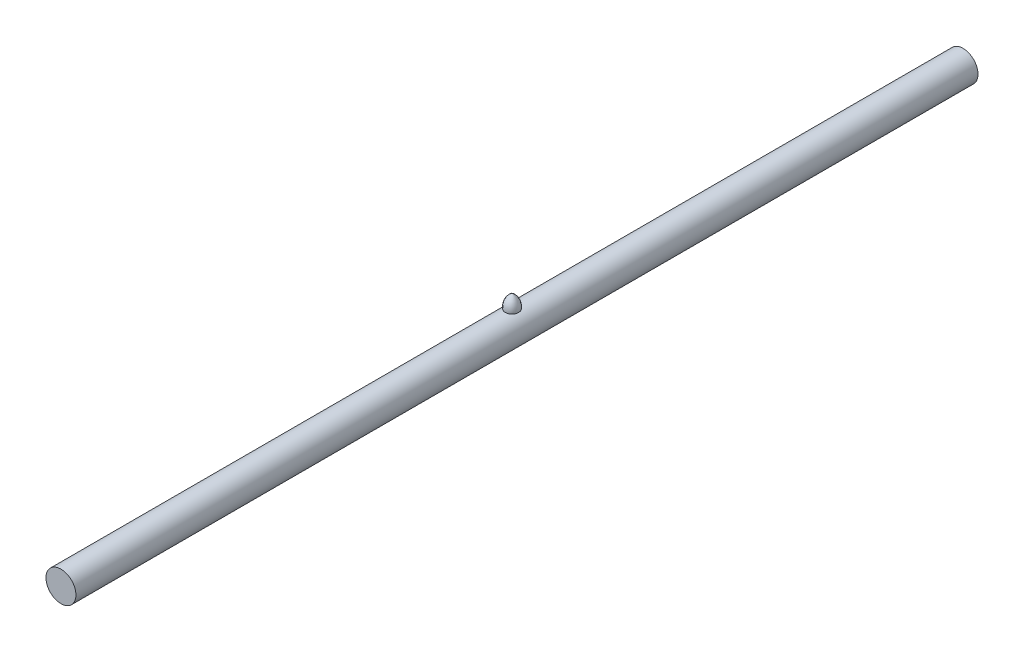
SolidWorks part; units mm, degrees
ref_plane "Front Plane" through (0, 0, 0) normal (0, 0, 1) x (1, 0, 0)
ref_plane "Top Plane" through (0, 0, 0) normal (0, 1, 0) x (1, 0, 0)
ref_plane "Right Plane" through (0, 0, 0) normal (1, 0, 0) x (0, 0, -1)
sketch "Sketch1" plane through (0, 0, 0) normal (0, 0, 1) x (1, 0, 0)
  circle A0 centre (0, 0) radius 2.8575
  dimension "D1" = 5.715
extrude "Boss-Extrude1" add sketch "Sketch1" along normal blind 172.085
ref_plane "Plane1" through (0, 0, 79.6925) normal (0, 0, 1) x (1, 0, 0)
sketch "Sketch2" plane through (0, 0, 0) normal (1, 0, 0) x (0, 0, -1)
  line L0 (-86.0425, 2.8575) -> (-86.0425, 5.3975) construction
  line L1 (0, 2.8575) -> (-172.085, 2.8575) construction
  line L2 (0, 2.8575) -> (-86.0425, 2.8575) construction
  line L3 (0, -2.8575) -> (0, 2.8575) construction
  line L6 (-84.7725, 2.8575) -> (-86.0425, 2.8575)
  line L7 (-86.0425, 5.3975) -> (-86.0425, 2.8575)
  arc A0 (-84.7725, 2.8575) -> (-86.0425, 5.3975) centre (-87.2912, 3.1856) ccw
  dimension "D1" = 86.0425
  dimension "D2" = 1.27
  dimension "D5" = 2.54
  dimension "D3" = 2.54
revolve "Revolve1" add sketch "Sketch2" angle 360 about L7
